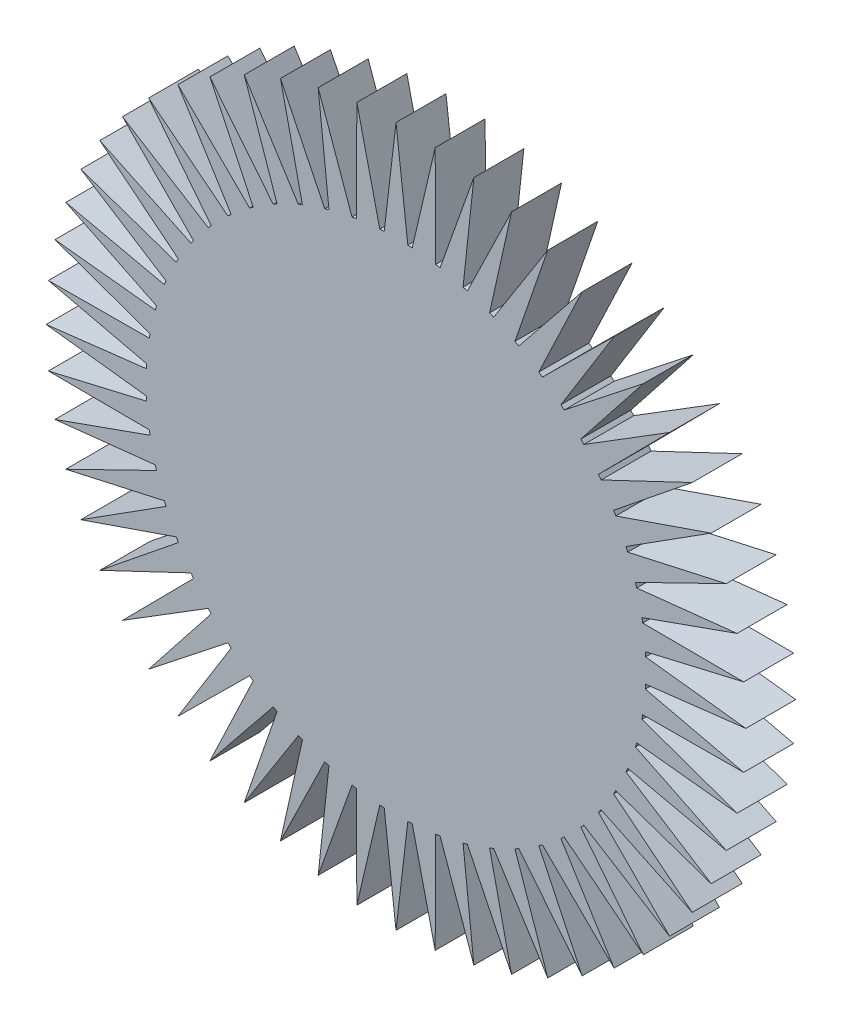
SolidWorks part; units mm, degrees
ref_plane "Plan de face" through (0, 0, 0) normal (0, 0, 1) x (1, 0, 0)
ref_plane "Plan de dessus" through (0, 0, 0) normal (0, 1, 0) x (1, 0, 0)
ref_plane "Plan de droite" through (0, 0, 0) normal (1, 0, 0) x (0, 0, -1)
sketch "Esquisse1" plane through (0, 0, 0) normal (0, 0, 1) x (1, 0, 0)
  circle A0 centre (0, 0) radius 35
  dimension "D1" = 70
extrude "Boss.-Extru.1" add sketch "Esquisse1" along normal blind 5
sketch "Esquisse3" plane through (0, 0, 5) normal (0, 0, 1) x (1, 0, 0)
  line L0 (0, 35) -> (0, 14.6737) construction
  line L1 (0, 35) -> (-1.1808, 24.9721)
  line L2 (0, 35) -> (1.1808, 24.9721)
  line L3 (3.9188, 34.7799) -> (1.6226, 24.9473)
  line L4 (3.9188, 34.7799) -> (3.9694, 24.6829)
  line L5 (7.7882, 34.1225) -> (4.4056, 24.6088)
  line L6 (7.7882, 34.1225) -> (6.7081, 24.0832)
  line L7 (11.5598, 33.0359) -> (7.1332, 23.9608)
  line L8 (11.5598, 33.0359) -> (9.3623, 23.1807)
  line L9 (15.1859, 31.5339) -> (9.7711, 23.0114)
  line L10 (15.1859, 31.5339) -> (11.8989, 21.9867)
  line L11 (18.6211, 29.6353) -> (12.2861, 21.7727)
  line L12 (18.6211, 29.6353) -> (14.2858, 20.5162)
  line L13 (21.8221, 27.3641) -> (14.6466, 20.2602)
  line L14 (21.8221, 27.3641) -> (16.4931, 18.7877)
  line L15 (24.7487, 24.7487) -> (16.823, 18.4929)
  line L16 (24.7487, 24.7487) -> (18.4929, 16.823)
  line L17 (27.3641, 21.8221) -> (18.7877, 16.4931)
  line L18 (27.3641, 21.8221) -> (20.2602, 14.6466)
  line L19 (29.6353, 18.6211) -> (20.5162, 14.2858)
  line L20 (29.6353, 18.6211) -> (21.7727, 12.2861)
  line L21 (31.5339, 15.1859) -> (21.9867, 11.8989)
  line L22 (31.5339, 15.1859) -> (23.0114, 9.7711)
  line L23 (33.0359, 11.5598) -> (23.1807, 9.3623)
  line L24 (33.0359, 11.5598) -> (23.9608, 7.1332)
  line L25 (34.1225, 7.7882) -> (24.0832, 6.7081)
  line L26 (34.1225, 7.7882) -> (24.6088, 4.4056)
  line L27 (34.7799, 3.9188) -> (24.6829, 3.9694)
  line L28 (34.7799, 3.9188) -> (24.9473, 1.6226)
  line L29 (35, 0) -> (24.9721, 1.1808)
  line L30 (35, 0) -> (24.9721, -1.1808)
  line L31 (34.7799, -3.9188) -> (24.9473, -1.6226)
  line L32 (34.7799, -3.9188) -> (24.6829, -3.9694)
  line L33 (34.1225, -7.7882) -> (24.6088, -4.4056)
  line L34 (34.1225, -7.7882) -> (24.0832, -6.7081)
  line L35 (33.0359, -11.5598) -> (23.9608, -7.1332)
  line L36 (33.0359, -11.5598) -> (23.1807, -9.3623)
  line L37 (31.5339, -15.1859) -> (23.0114, -9.7711)
  line L38 (31.5339, -15.1859) -> (21.9867, -11.8989)
  line L39 (29.6353, -18.6211) -> (21.7727, -12.2861)
  line L40 (29.6353, -18.6211) -> (20.5162, -14.2858)
  line L41 (27.3641, -21.8221) -> (20.2602, -14.6466)
  line L42 (27.3641, -21.8221) -> (18.7877, -16.4931)
  line L43 (24.7487, -24.7487) -> (18.4929, -16.823)
  line L44 (24.7487, -24.7487) -> (16.823, -18.4929)
  line L45 (21.8221, -27.3641) -> (16.4931, -18.7877)
  line L46 (21.8221, -27.3641) -> (14.6466, -20.2602)
  line L47 (18.6211, -29.6353) -> (14.2858, -20.5162)
  line L48 (18.6211, -29.6353) -> (12.2861, -21.7727)
  line L49 (15.1859, -31.5339) -> (11.8989, -21.9867)
  line L50 (15.1859, -31.5339) -> (9.7711, -23.0114)
  line L51 (11.5598, -33.0359) -> (9.3623, -23.1807)
  line L52 (11.5598, -33.0359) -> (7.1332, -23.9608)
  line L53 (7.7882, -34.1225) -> (6.7081, -24.0832)
  line L54 (7.7882, -34.1225) -> (4.4056, -24.6088)
  line L55 (3.9188, -34.7799) -> (3.9694, -24.6829)
  line L56 (3.9188, -34.7799) -> (1.6226, -24.9473)
  line L57 (0, -35) -> (1.1808, -24.9721)
  line L58 (0, -35) -> (-1.1808, -24.9721)
  line L59 (-3.9188, -34.7799) -> (-1.6226, -24.9473)
  line L60 (-3.9188, -34.7799) -> (-3.9694, -24.6829)
  line L61 (-7.7882, -34.1225) -> (-4.4056, -24.6088)
  line L62 (-7.7882, -34.1225) -> (-6.7081, -24.0832)
  line L63 (-11.5598, -33.0359) -> (-7.1332, -23.9608)
  line L64 (-11.5598, -33.0359) -> (-9.3623, -23.1807)
  line L65 (-15.1859, -31.5339) -> (-9.7711, -23.0114)
  line L66 (-15.1859, -31.5339) -> (-11.8989, -21.9867)
  line L67 (-18.6211, -29.6353) -> (-12.2861, -21.7727)
  line L68 (-18.6211, -29.6353) -> (-14.2858, -20.5162)
  line L69 (-21.8221, -27.3641) -> (-14.6466, -20.2602)
  line L70 (-21.8221, -27.3641) -> (-16.4931, -18.7877)
  line L71 (-24.7487, -24.7487) -> (-16.823, -18.4929)
  line L72 (-24.7487, -24.7487) -> (-18.4929, -16.823)
  line L73 (-27.3641, -21.8221) -> (-18.7877, -16.4931)
  line L74 (-27.3641, -21.8221) -> (-20.2602, -14.6466)
  line L75 (-29.6353, -18.6211) -> (-20.5162, -14.2858)
  line L76 (-29.6353, -18.6211) -> (-21.7727, -12.2861)
  line L77 (-31.5339, -15.1859) -> (-21.9867, -11.8989)
  line L78 (-31.5339, -15.1859) -> (-23.0114, -9.7711)
  line L79 (-33.0359, -11.5598) -> (-23.1807, -9.3623)
  line L80 (-33.0359, -11.5598) -> (-23.9608, -7.1332)
  line L81 (-34.1225, -7.7882) -> (-24.0832, -6.7081)
  line L82 (-34.1225, -7.7882) -> (-24.6088, -4.4056)
  line L83 (-34.7799, -3.9188) -> (-24.6829, -3.9694)
  line L84 (-34.7799, -3.9188) -> (-24.9473, -1.6226)
  line L85 (-35, 0) -> (-24.9721, -1.1808)
  line L86 (-35, 0) -> (-24.9721, 1.1808)
  line L87 (-34.7799, 3.9188) -> (-24.9473, 1.6226)
  line L88 (-34.7799, 3.9188) -> (-24.6829, 3.9694)
  line L89 (-34.1225, 7.7882) -> (-24.6088, 4.4056)
  line L90 (-34.1225, 7.7882) -> (-24.0832, 6.7081)
  line L91 (-33.0359, 11.5598) -> (-23.9608, 7.1332)
  line L92 (-33.0359, 11.5598) -> (-23.1807, 9.3623)
  line L93 (-31.5339, 15.1859) -> (-23.0114, 9.7711)
  line L94 (-31.5339, 15.1859) -> (-21.9867, 11.8989)
  line L95 (-29.6353, 18.6211) -> (-21.7727, 12.2861)
  line L96 (-29.6353, 18.6211) -> (-20.5162, 14.2858)
  line L97 (-27.3641, 21.8221) -> (-20.2602, 14.6466)
  line L98 (-27.3641, 21.8221) -> (-18.7877, 16.4931)
  line L99 (-24.7487, 24.7487) -> (-18.4929, 16.823)
  line L100 (-24.7487, 24.7487) -> (-16.823, 18.4929)
  line L101 (-21.8221, 27.3641) -> (-16.4931, 18.7877)
  line L102 (-21.8221, 27.3641) -> (-14.6466, 20.2602)
  line L103 (-18.6211, 29.6353) -> (-14.2858, 20.5162)
  line L104 (-18.6211, 29.6353) -> (-12.2861, 21.7727)
  line L105 (-15.1859, 31.5339) -> (-11.8989, 21.9867)
  line L106 (-15.1859, 31.5339) -> (-9.7711, 23.0114)
  line L107 (-11.5598, 33.0359) -> (-9.3623, 23.1807)
  line L108 (-11.5598, 33.0359) -> (-7.1332, 23.9608)
  line L109 (-7.7882, 34.1225) -> (-6.7081, 24.0832)
  line L110 (-7.7882, 34.1225) -> (-4.4056, 24.6088)
  line L111 (-3.9188, 34.7799) -> (-3.9694, 24.6829)
  line L112 (-3.9188, 34.7799) -> (-1.6226, 24.9473)
  circle A0 centre (0, 0) radius 25
  circle A1 centre (0, 0) radius 35 construction
  point P177 (0, 0)
  circle M3 centre (0, 0) radius 35
  dimension "D1" = 50
  dimension "D2" = 10
  dimension "D3" = 10.0279
  dimension "D4" = 56
extrude "Enlèv. mat.-Extru.2" cut sketch "Esquisse3" against normal blind 5 contours A0 L105 L104 M3 | A0 L107 L106 M3 | A0 L109 L108 M3 | A0 L111 L110 M3 | A0 L1 L112 M3 | A0 L3 L2 M3 | A0 L5 L4 M3 | A0 L7 L6 M3 | A0 L9 L8 M3 | A0 L11 L10 M3 | A0 L13 L12 M3 | A0 L15 L14 M3 | A0 L103 L102 M3 | A0 L101 L100 M3 | A0 L99 L98 M3 | A0 L97 L96 M3 | A0 L95 L94 M3 | A0 L93 L92 M3 | A0 L91 L90 M3 | A0 L89 L88 M3 | A0 L87 L86 M3 | A0 L85 L84 M3 | A0 L83 L82 M3 | A0 L81 L80 M3 | A0 L79 L78 M3 | A0 L77 L76 M3 | A0 L75 L74 M3 | A0 L73 L72 M3 | A0 L71 L70 M3 | A0 L69 L68 M3 | A0 L67 L66 M3 | A0 L65 L64 M3 | A0 L63 L62 M3 | A0 L61 L60 M3 | A0 L59 L58 M3 | A0 L57 L56 M3 | A0 L55 L54 M3 | A0 L53 L52 M3 | A0 L51 L50 M3 | A0 L49 L48 M3 | A0 L47 L46 M3 | A0 L45 L44 M3 | A0 L43 L42 M3 | A0 L41 L40 M3 | A0 L39 L38 M3 | A0 L37 L36 M3 | A0 L35 L34 M3 | A0 L33 L32 M3 | A0 L17 L16 M3 | A0 L19 L18 M3 | A0 L21 L20 M3 | A0 L23 L22 M3 | A0 L25 L24 M3 | A0 L27 L26 M3 | A0 L29 L28 M3 | A0 L31 L30 M3
